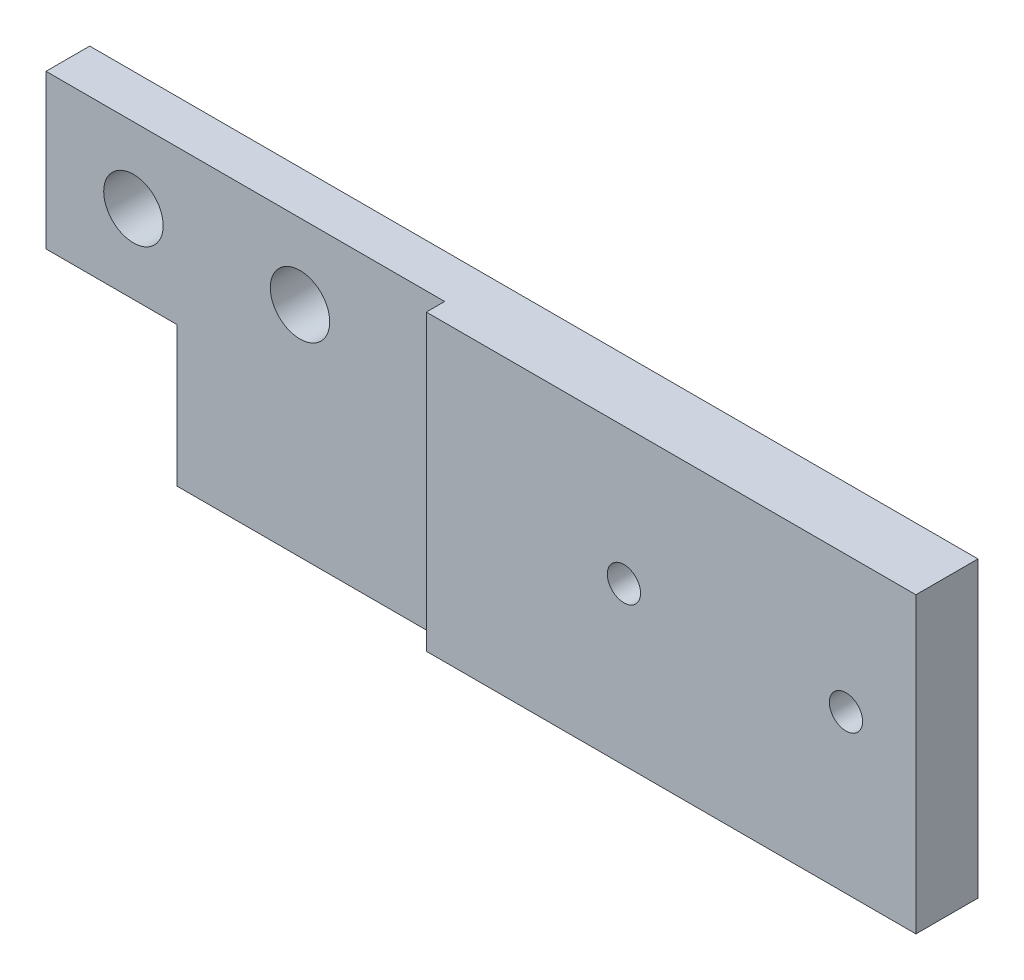
SolidWorks part; units mm, degrees
ref_plane "Front Plane" through (0, 0, 0) normal (0, 0, 1) x (1, 0, 0)
ref_plane "Top Plane" through (0, 0, 0) normal (0, 1, 0) x (1, 0, 0)
ref_plane "Right Plane" through (0, 0, 0) normal (1, 0, 0) x (0, 0, -1)
sketch "Sketch1" plane through (0, 0, 0) normal (0, 0, 1) x (1, 0, 0)
  line L1 (50.8, -16.7996) -> (-50.8, -16.7996)
  line L2 (50.8, -16.7996) -> (50.8, 16.7996)
  line L3 (50.8, 16.7996) -> (-50.8, 16.7996)
  line L4 (-50.8, -16.7996) -> (-50.8, 16.7996)
  line L5 (50.8, -16.7996) -> (-50.8, 16.7996) construction
  line L6 (50.8, 16.7996) -> (-50.8, -16.7996) construction
  point P0 (0, 0)
  dimension "D1" = 33.5991
  dimension "D2" = 101.6
extrude "Boss-Extrude1" add sketch "Sketch1" along normal blind 5
sketch "Sketch2" plane through (0, 0, 0) normal (0, 0, -1) x (-1, 0, 0)
  line L0 (50.8, 16.7996) -> (50.8, -16.7996) construction
  line L1 (50.8, 8.2004) -> (-50.8, 8.2004) construction
  line L2 (-50.8, -16.7996) -> (-50.8, 16.7996) construction
  line L3 (-17.4, 1.2004) -> (-42.8, 1.2004) construction
  line L4 (50.8, -16.7996) -> (-50.8, -16.7996) construction
  circle A0 centre (40.8, 8.2004) radius 3.4
  circle A1 centre (21.75, 8.2004) radius 3.4
  circle A2 centre (-17.4, 1.2004) radius 1.9
  circle A3 centre (-42.8, 1.2004) radius 1.9
  point P17 (0, 0)
  dimension "D3" = 6.8
  dimension "D8" = 3.8
  dimension "D1" = 10
  dimension "D2" = 19.05
  dimension "D4" = 25
  dimension "D5" = 25.4
  dimension "D6" = 8
  dimension "D7" = 18
extrude "Cut-Extrude1" cut sketch "Sketch2" against normal up to surface (5 mm away) up to face at (0, 0, 5)
sketch "Sketch5" plane through (0, 0, 0) normal (0, 0, -1) x (-1, 0, 0)
  line L10 (50.8, -16.7996) -> (35.8, -16.7996)
  line L11 (50.8, -16.7996) -> (50.8, -0.7996)
  line L12 (50.8, -0.7996) -> (35.8, -0.7996)
  line L13 (35.8, -16.7996) -> (35.8, -0.7996)
  line L14 (50.8, 16.7996) -> (50.8, -16.7996) construction
  point P3 (36.9608, -16.4658)
  point P5 (50.8, -16.7996)
  point P8 (46.3, -7.7996)
  point P10 (0, 0)
  point P11 (50.8, -14.5411)
  dimension "D2" = 15
  dimension "D1" = 16
fillet "Fillet1" [suppressed] radius 1
extrude "Cut-Extrude4" cut sketch "Sketch5" against normal blind 5 contours L13 L12 L11 L10
fillet "Fillet2" [suppressed] radius 5
sketch "Sketch7" plane through (0, 0, 5) normal (0, 0, 1) x (1, 0, 0)
  line L1 (50.8, -16.7996) -> (-5.2, -16.7996)
  line L2 (50.8, -16.7996) -> (50.8, 16.7996)
  line L3 (50.8, 16.7996) -> (-5.2, 16.7996)
  line L4 (-5.2, -16.7996) -> (-5.2, 16.7996)
  line L6 (-50.8, 16.7996) -> (-50.8, -0.7996)
  line L7 (-50.8, -0.7996) -> (-35.8, -0.7996)
  line L8 (-35.8, -0.7996) -> (-35.8, -16.7996)
  line L9 (-35.8, -16.7996) -> (50.8, -16.7996)
  line L10 (50.8, -16.7996) -> (50.8, 16.7996)
  line L11 (50.8, 16.7996) -> (-50.8, 16.7996)
  line L12 (-50.8, 16.7996) -> (-50.8, -0.7996)
  line L13 (-50.8, -0.7996) -> (-35.8, -0.7996)
  line L14 (-35.8, -0.7996) -> (-35.8, -16.7996)
  line L15 (-35.8, -16.7996) -> (50.8, -16.7996)
  line L16 (50.8, -16.7996) -> (50.8, 16.7996)
  line L17 (50.8, 16.7996) -> (-50.8, 16.7996)
  circle M14 centre (17.4, 1.2004) radius 1.9
  circle M15 centre (42.8, 1.2004) radius 1.9
  line M22 (-35.8, -16.7996) -> (50.8, -16.7996)
  line M23 (50.8, -16.7996) -> (50.8, 16.7996)
  line M24 (50.8, 16.7996) -> (-50.8, 16.7996)
  dimension "D2" = 56
  dimension "D1" = 0
extrude "Boss-Extrude2" add sketch "Sketch7" along normal blind 2.1 contours L4 M22 M23 M24 M14 M15
